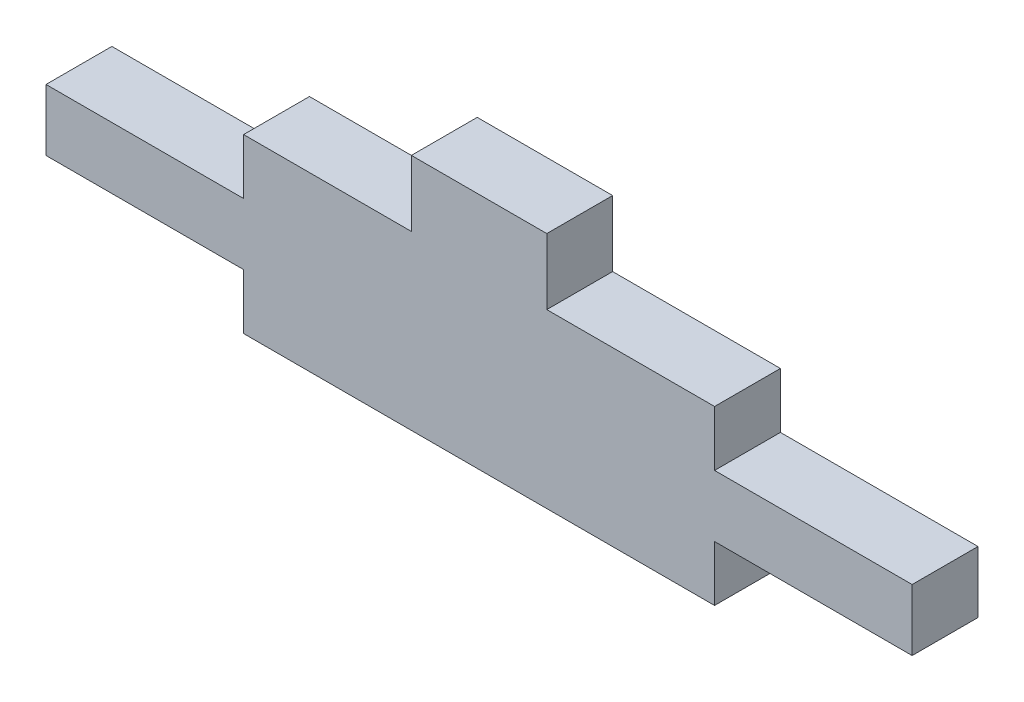
SolidWorks part; units mm, degrees
ref_plane "Front Plane" through (0, 0, 0) normal (0, 0, 1) x (1, 0, 0)
ref_plane "Top Plane" through (0, 0, 0) normal (0, 1, 0) x (1, 0, 0)
ref_plane "Right Plane" through (0, 0, 0) normal (1, 0, 0) x (0, 0, -1)
sketch "Model" plane through (0, 0, 0) normal (0, 0, 1) x (1, 0, 0)
  line L320 (29.68, 19.35) -> (29.68, 14)
  line L321 (40.68, 19.35) -> (29.68, 19.35)
  line L322 (40.68, 14) -> (40.68, 19.35)
  line L323 (54.31, 14) -> (40.68, 14)
  line L324 (54.31, 9.5) -> (54.31, 14)
  line L325 (70.36, 9.5) -> (54.31, 9.5)
  line L326 (70.36, 4.5) -> (70.36, 9.5)
  line L327 (54.31, 4.5) -> (70.36, 4.5)
  line L328 (54.31, 0) -> (54.31, 4.5)
  line L329 (16.05, 0) -> (54.31, 0)
  line L330 (16.05, 4.5) -> (16.05, 0)
  line L331 (0, 4.5) -> (16.05, 4.5)
  line L332 (0, 9.5) -> (0, 4.5)
  line L333 (16.05, 9.5) -> (0, 9.5)
  line L334 (16.05, 14) -> (16.05, 9.5)
  line L335 (29.68, 14) -> (16.05, 14)
extrude "Boss-Extrude1" add sketch "Model" along normal blind 5.35
